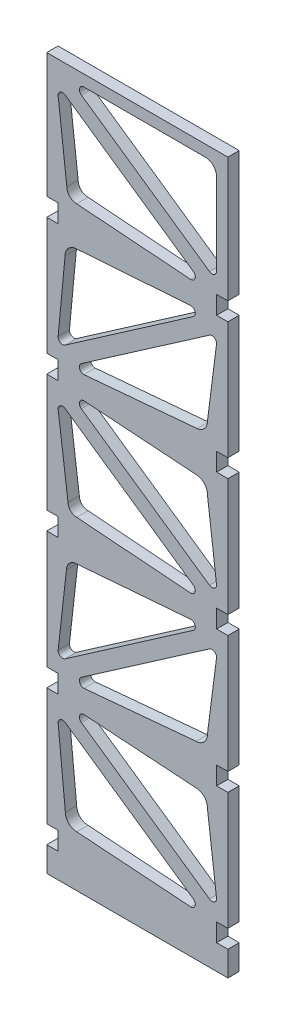
SolidWorks part; units mm, degrees
material "Balsa"
ref_plane "Front Plane" through (0, 0, 0) normal (0, 0, 1) x (1, 0, 0)
ref_plane "Top Plane" through (0, 0, 0) normal (0, 1, 0) x (1, 0, 0)
ref_plane "Right Plane" through (0, 0, 0) normal (1, 0, 0) x (0, 0, -1)
sketch "Model" plane through (0, 0, 0) normal (0, 0, 1) x (1, 0, 0)
  line L0 (83.8206, 83.4119) -> (20.8312, 87.63)
  line L1 (95.25, 35.3278) -> (90.0765, 77.0619)
  line L2 (19.3854, 83.0016) -> (91.2642, 33.2394)
  line L3 (11.0347, 153.0035) -> (6.35, 111.5278)
  line L4 (80.7688, 163.83) -> (16.773, 158.7418)
  line L5 (10.3358, 109.4394) -> (82.2146, 159.2016)
  line L6 (84.1002, 235.6301) -> (20.8312, 240.03)
  line L7 (95.25, 187.7278) -> (90.0868, 229.2801)
  line L8 (19.3854, 235.4016) -> (91.2642, 185.6394)
  line L9 (16.773, 181.4025) -> (80.7688, 176.53)
  line L10 (6.35, 228.8322) -> (11.91, 186.2655)
  line L11 (82.2146, 181.1584) -> (10.3358, 230.9206)
  line L12 (91.2642, 154.7206) -> (19.3854, 104.9584)
  line L13 (90.0758, 112.418) -> (95.25, 152.6322)
  line L14 (20.8312, 100.33) -> (83.7258, 106.068)
  line L15 (10.2715, 305.2328) -> (6.35, 263.9278)
  line L16 (80.7688, 316.23) -> (16.773, 311.7343)
  line L17 (10.3358, 261.8394) -> (82.2146, 311.6016)
  line L18 (88.9, 392.43) -> (20.8312, 392.43)
  line L19 (95.25, 340.1278) -> (95.25, 386.08)
  line L20 (19.3854, 387.8016) -> (91.2642, 338.0394)
  line L21 (16.773, 333.7002) -> (80.7688, 328.93)
  line L22 (6.35, 381.2322) -> (11.2542, 339.219)
  line L23 (82.2146, 333.5584) -> (10.3358, 383.3206)
  line L24 (16.773, 28.6153) -> (80.7688, 24.13)
  line L25 (6.35, 76.4322) -> (10.423, 34.9653)
  line L26 (82.2146, 28.7584) -> (10.3358, 78.5206)
  line L27 (91.2642, 307.1206) -> (19.3854, 257.3584)
  line L28 (90.1025, 264.6247) -> (95.25, 305.0322)
  line L29 (20.8312, 252.73) -> (84.3093, 258.2747)
  line L30 (0, 398.78) -> (0, 0)
  line L31 (0, 0) -> (101.6, 0)
  line L32 (101.6, 398.78) -> (101.6, 0)
  line L33 (0, 398.78) -> (101.6, 398.78)
  arc A0 (90.0765, 77.0619) -> (83.8206, 83.4119) centre (83.7258, 77.0619) ccw
  arc A1 (91.2642, 33.2394) -> (95.25, 35.3278) centre (92.71, 35.3278) ccw
  arc A2 (20.8312, 87.63) -> (19.3854, 83.0016) centre (20.8312, 85.09) ccw
  arc A3 (16.773, 158.7418) -> (11.0347, 153.0035) centre (16.773, 153.0035) ccw
  arc A4 (82.2146, 159.2016) -> (80.7688, 163.83) centre (80.7688, 161.29) ccw
  arc A5 (6.35, 111.5278) -> (10.3358, 109.4394) centre (8.89, 111.5278) ccw
  arc A6 (90.0868, 229.2801) -> (84.1002, 235.6301) centre (83.7258, 229.2801) ccw
  arc A7 (91.2642, 185.6394) -> (95.25, 187.7278) centre (92.71, 187.7278) ccw
  arc A8 (20.8312, 240.03) -> (19.3854, 235.4016) centre (20.8312, 237.49) ccw
  arc A9 (11.91, 186.2655) -> (16.773, 181.4025) centre (16.773, 186.2655) ccw
  arc A10 (10.3358, 230.9206) -> (6.35, 228.8322) centre (8.89, 228.8322) ccw
  arc A11 (80.7688, 176.53) -> (82.2146, 181.1584) centre (80.7688, 179.07) ccw
  arc A12 (95.25, 152.6322) -> (91.2642, 154.7206) centre (92.71, 152.6322) ccw
  arc A13 (83.7258, 106.068) -> (90.0758, 112.418) centre (83.7258, 112.418) ccw
  arc A14 (19.3854, 104.9584) -> (20.8312, 100.33) centre (20.8312, 102.87) ccw
  arc A15 (16.773, 311.7343) -> (10.2715, 305.2328) centre (16.773, 305.2328) ccw
  arc A16 (82.2146, 311.6016) -> (80.7688, 316.23) centre (80.7688, 313.69) ccw
  arc A17 (6.35, 263.9278) -> (10.3358, 261.8394) centre (8.89, 263.9278) ccw
  arc A18 (95.25, 386.08) -> (88.9, 392.43) centre (88.9, 386.08) ccw
  arc A19 (91.2642, 338.0394) -> (95.25, 340.1278) centre (92.71, 340.1278) ccw
  arc A20 (20.8312, 392.43) -> (19.3854, 387.8016) centre (20.8312, 389.89) ccw
  arc A21 (11.2542, 339.219) -> (16.773, 333.7002) centre (16.773, 339.219) ccw
  arc A22 (10.3358, 383.3206) -> (6.35, 381.2322) centre (8.89, 381.2322) ccw
  arc A23 (80.7688, 328.93) -> (82.2146, 333.5584) centre (80.7688, 331.47) ccw
  arc A24 (10.423, 34.9653) -> (16.773, 28.6153) centre (16.773, 34.9653) ccw
  arc A25 (10.3358, 78.5206) -> (6.35, 76.4322) centre (8.89, 76.4322) ccw
  arc A26 (80.7688, 24.13) -> (82.2146, 28.7584) centre (80.7688, 26.67) ccw
  arc A27 (95.25, 305.0322) -> (91.2642, 307.1206) centre (92.71, 305.0322) ccw
  arc A28 (84.3093, 258.2747) -> (90.1025, 264.6247) centre (83.7258, 264.6247) ccw
  arc A29 (19.3854, 257.3584) -> (20.8312, 252.73) centre (20.8312, 255.27) ccw
  point P94 (0, 0)
  point P95 (0, 0)
  point P96 (0, 0)
  point P97 (0, 0)
  point P98 (0, 0)
extrude "Boss-Extrude1" add sketch "Model" along normal blind 6.35
sketch "Sketch1" plane through (0, 0, 6.35) normal (0, 0, 1) x (1, 0, 0)
  line L0 (101.6, 0) -> (101.6, 398.78) construction
  line L1 (101.6, 328.93) -> (95.25, 328.93)
  line L2 (101.6, 328.93) -> (101.6, 318.77)
  line L3 (101.6, 318.77) -> (95.25, 318.77)
  line L4 (95.25, 328.93) -> (95.25, 318.77)
  line L5 (0, 398.78) -> (0, 0) construction
  line L6 (0, 252.73) -> (6.35, 252.73)
  line L7 (0, 252.73) -> (0, 242.57)
  line L8 (0, 242.57) -> (6.35, 242.57)
  line L9 (6.35, 252.73) -> (6.35, 242.57)
  line L10 (16.773, 333.7002) -> (80.7688, 328.93) construction
  line L11 (101.6, 176.53) -> (95.25, 176.53)
  line L12 (101.6, 176.53) -> (101.6, 166.37)
  line L13 (101.6, 166.37) -> (95.25, 166.37)
  line L14 (95.25, 176.53) -> (95.25, 166.37)
  line L15 (0, 100.33) -> (6.35, 100.33)
  line L16 (0, 100.33) -> (0, 90.17)
  line L17 (0, 90.17) -> (6.35, 90.17)
  line L18 (6.35, 100.33) -> (6.35, 90.17)
  line L19 (20.8312, 252.73) -> (84.3093, 258.2747) construction
  line L20 (16.773, 181.4025) -> (80.7688, 176.53) construction
  line L21 (20.8312, 100.33) -> (83.7258, 106.068) construction
  line L22 (16.773, 28.6153) -> (80.7688, 24.13) construction
  line L23 (0, 328.93) -> (6.35, 328.93)
  line L24 (0, 328.93) -> (0, 318.77)
  line L25 (0, 318.77) -> (6.35, 318.77)
  line L26 (6.35, 328.93) -> (6.35, 318.77)
  line L27 (101.6, 252.73) -> (95.25, 252.73)
  line L28 (101.6, 252.73) -> (101.6, 242.57)
  line L29 (101.6, 242.57) -> (95.25, 242.57)
  line L30 (95.25, 252.73) -> (95.25, 242.57)
  line L31 (0, 176.53) -> (6.35, 176.53)
  line L32 (0, 176.53) -> (0, 166.37)
  line L33 (0, 166.37) -> (6.35, 166.37)
  line L34 (6.35, 176.53) -> (6.35, 166.37)
  line L35 (101.6, 100.33) -> (95.25, 100.33)
  line L36 (101.6, 100.33) -> (101.6, 90.17)
  line L37 (101.6, 90.17) -> (95.25, 90.17)
  line L38 (95.25, 100.33) -> (95.25, 90.17)
  line L39 (0, 24.13) -> (6.35, 24.13)
  line L40 (0, 24.13) -> (0, 13.97)
  line L41 (0, 13.97) -> (6.35, 13.97)
  line L42 (6.35, 24.13) -> (6.35, 13.97)
  line L43 (101.6, 24.13) -> (95.25, 24.13)
  line L44 (101.6, 24.13) -> (101.6, 13.97)
  line L45 (101.6, 13.97) -> (95.25, 13.97)
  line L46 (95.25, 24.13) -> (95.25, 13.97)
  point P54 (0, 0)
  dimension "D1" = 6.35
  dimension "D2" = 10.16
  dimension "D3" = 10.16
  dimension "D4" = 6.35
  dimension "D5" = 6.35
  dimension "D6" = 10.16
  dimension "D7" = 6.35
  dimension "D8" = 10.16
  dimension "D9" = 10.16
  dimension "D10" = 10.16
extrude "Cut-Extrude1" cut sketch "Sketch1" against normal up to surface (6.35 mm away) contours L43 L46 L45 L44 | L18 L15 L16 L17 | L11 L14 L13 L12 | L34 L31 L32 L33 | L27 L30 L29 L28 | L26 L23 L24 L25 | L41 L42 L39 L40 | L35 L38 L37 L36 | L9 L8 L7 L6 | L1 L4 L3 L2 up to face at (50.8, 199.39, 0)
equation "\"thick\"=0.25"
equation "\"D1@Boss-Extrude1\"=\"thick\""
